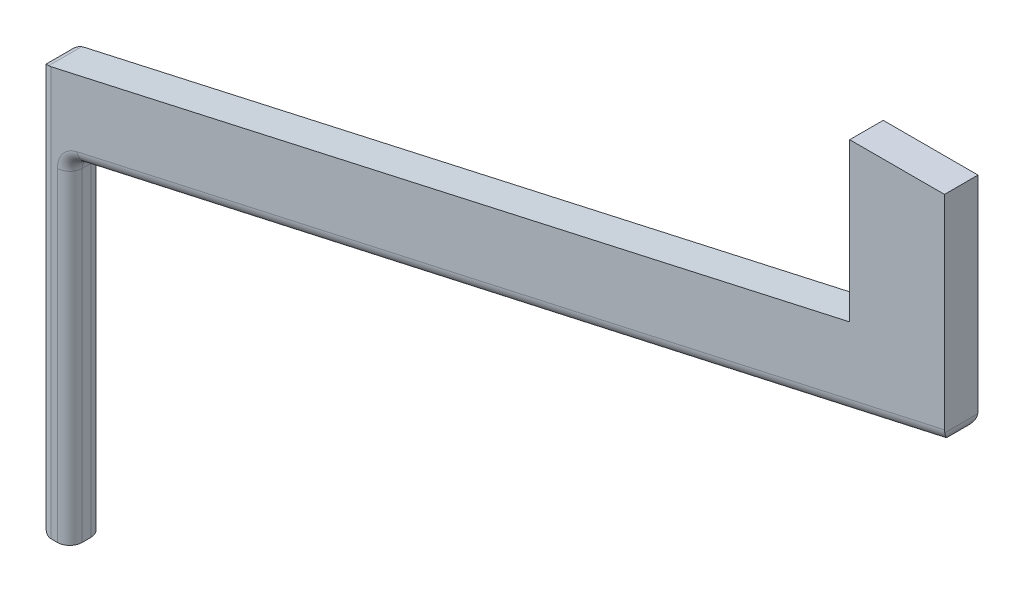
SolidWorks part; units mm, degrees
ref_plane "Plano frontal" through (0, 0, 0) normal (0, 0, 1) x (1, 0, 0)
ref_plane "Plano superior" through (0, 0, 0) normal (0, 1, 0) x (1, 0, 0)
ref_plane "Plano direito" through (0, 0, 0) normal (1, 0, 0) x (0, 0, -1)
sketch "Esboço1" plane through (0, 0, 0) normal (0, 0, 1) x (1, 0, 0)
  line L0 (0, 0) -> (0, 3.2708)
  line L1 (0, 3.2708) -> (6.5313, 4.7292)
  line L2 (6.5313, 4.7292) -> (6.5313, 6)
  line L3 (6.5313, 6) -> (7.2945, 6)
  line L4 (0.25, 0) -> (0, 0)
  line L5 (0.25, 0) -> (0.25, 2.6893)
  line L6 (0.25, 2.6893) -> (6.6292, 4.1077)
  line L7 (6.6292, 4.1077) -> (7.2945, 4.2557)
  line L8 (7.2945, 4.2557) -> (7.2945, 6)
  dimension "D1" = 6
  dimension "D2" = 0.25
extrude "Ressalto-extrusão1" add sketch "Esboço1" along normal blind 0.27
fillet "Filete5" radius 0.1 10 edges at (0.25, 1.3446, 0.27) (0.25, 1.3446, 0) (0.25, 2.6893, 0.135) (3.7723, 3.4725, 0.27) (7.2945, 4.2557, 0.135) (3.7723, 3.4725, 0) (0, 3.2708, 0.135) (0, 1.6354, 0.27) (0, 0, 0.135) (0, 1.6354, 0)
